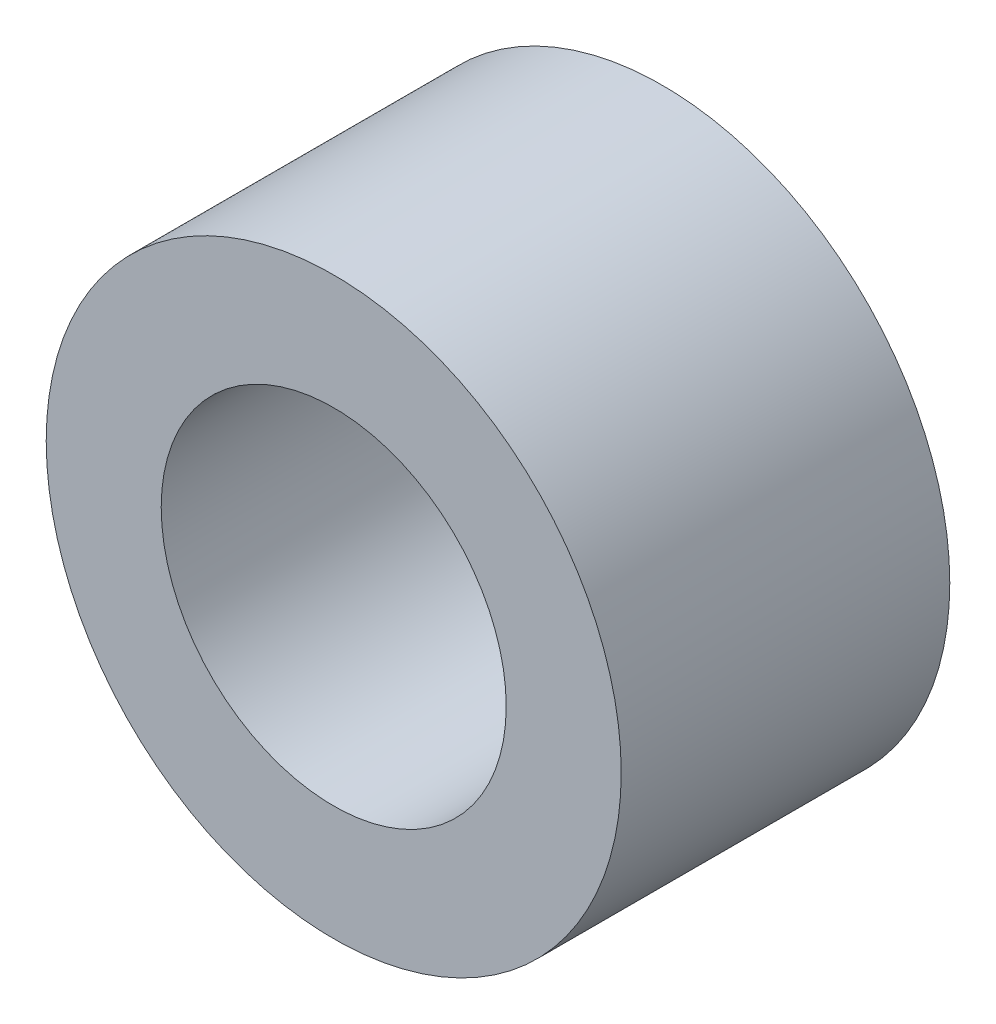
SolidWorks part; units mm, degrees
ref_plane "前视基准面" through (0, 0, 0) normal (0, 0, 1) x (1, 0, 0)
ref_plane "上视基准面" through (0, 0, 0) normal (0, 1, 0) x (1, 0, 0)
ref_plane "右视基准面" through (0, 0, 0) normal (1, 0, 0) x (0, 0, -1)
sketch "草图1" plane through (0, 0, 0) normal (0, 0, 1) x (1, 0, 0)
  circle A0 centre (0, 0) radius 3.5
  circle A1 centre (0, 0) radius 2.1
  dimension "D1" = 7
  dimension "D2" = 4.2
extrude "凸台-拉伸1" add sketch "草图1" along normal blind 4
